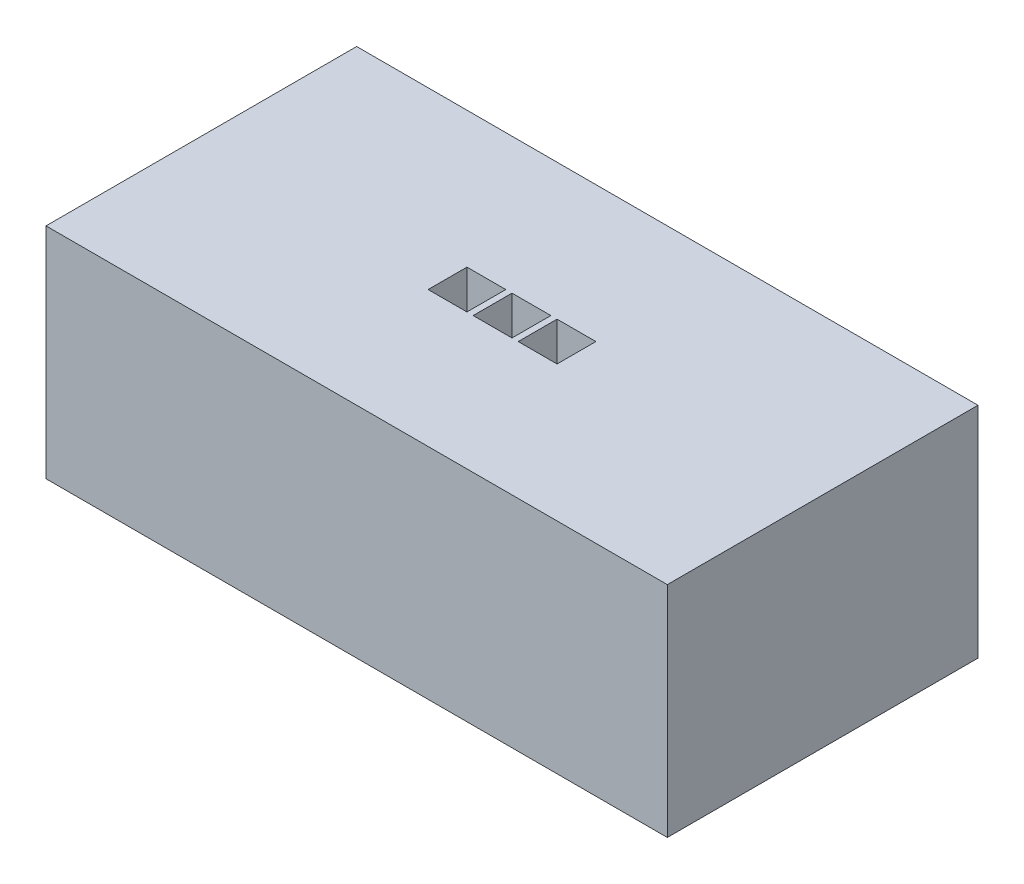
SolidWorks part; units mm, degrees
ref_plane "Plan de face" through (0, 0, 0) normal (0, 0, 1) x (1, 0, 0)
ref_plane "Plan de dessus" through (0, 0, 0) normal (0, 1, 0) x (1, 0, 0)
ref_plane "Plan de droite" through (0, 0, 0) normal (1, 0, 0) x (0, 0, -1)
sketch "Esquisse1" plane through (0, 0, 0) normal (0, 1, 0) x (1, 0, 0)
  line L1 (20, 10) -> (-20, 10)
  line L2 (20, 10) -> (20, -10)
  line L3 (20, -10) -> (-20, -10)
  line L4 (-20, 10) -> (-20, -10)
  line L5 (20, 10) -> (-20, -10) construction
  line L6 (20, -10) -> (-20, 10) construction
  point P0 (0, 0)
  dimension "D1" = 20
  dimension "D2" = 40
extrude "Boss.-Extru.2" add sketch "Esquisse1" along normal blind 14.1 contours L4 L3 L2 L1
sketch "Esquisse2" plane through (0, 14.1, 0) normal (0, 1, 0) x (1, 0, 0)
  line L0 (-1.65, 0) -> (-1.25, 0) construction
  line L2 (1.25, 0) -> (1.65, 0) construction
  line L106 (-4.15, 1.25) -> (-1.65, 1.25)
  line L107 (-4.15, 1.25) -> (-4.15, -1.25)
  line L108 (-4.15, -1.25) -> (-1.65, -1.25)
  line L109 (-1.65, 1.25) -> (-1.65, -1.25)
  line L112 (-1.25, 1.25) -> (1.25, 1.25)
  line L113 (-1.25, 1.25) -> (-1.25, -1.25)
  line L114 (-1.25, -1.25) -> (1.25, -1.25)
  line L115 (1.25, 1.25) -> (1.25, -1.25)
  line L118 (1.65, 1.25) -> (4.15, 1.25)
  line L119 (1.65, 1.25) -> (1.65, -1.25)
  line L120 (1.65, -1.25) -> (4.15, -1.25)
  line L121 (4.15, 1.25) -> (4.15, -1.25)
  point P2 (0, 0)
  point P10 (2.9, 0)
  point P17 (-2.9, 0)
  point P24 (0, 0)
  point P29 (2.9, 0)
  dimension "D4" = 2.5
extrude "Enlèv. mat.-Extru.1" cut sketch "Esquisse2" against normal through all
